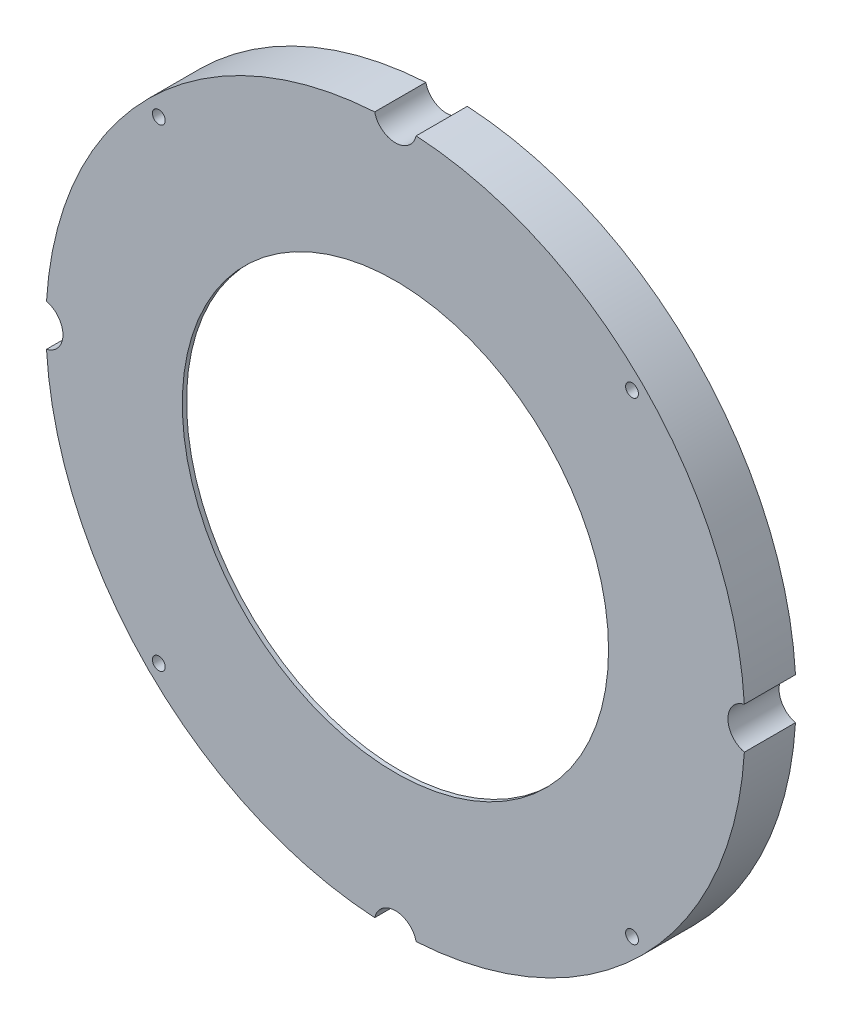
SolidWorks part; units mm, degrees
ref_plane "Front Plane" through (0, 0, 0) normal (0, 0, 1) x (1, 0, 0)
ref_plane "Top Plane" through (0, 0, 0) normal (0, 1, 0) x (1, 0, 0)
ref_plane "Right Plane" through (0, 0, 0) normal (1, 0, 0) x (0, 0, -1)
sketch "Sketch1" plane through (0, 0, 0) normal (0, 0, 1) x (1, 0, 0)
  circle A0 centre (0, 0) radius 50
  circle A1 centre (0, 0) radius 82
extrude "Boss-Extrude1" add sketch "Sketch1" along normal blind 1
sketch "Sketch3" plane through (0, 0, 0) normal (0, 0, -1) x (-1, 0, 0)
  circle A0 centre (0, 0) radius 75
  circle A1 centre (0, 0) radius 82
extrude "Boss-Extrude3" add sketch "Sketch3" along normal blind 11
sketch "Sketch4" plane through (0, 0, 1) normal (0, 0, 1) x (1, 0, 0)
  circle A0 centre (0, 83) radius 5
extrude "Cut-Extrude1" cut sketch "Sketch4" against normal through all
pattern_circular "CirPattern1" count 4 every 90 about axis through (0, 0, 0) along (0, 0, 1) of "Cut-Extrude1"
sketch "Sketch5" plane through (0, 0, -11) normal (0, 0, -1) x (-1, 0, 0)
  circle A0 centre (55.5079, 55.5079) radius 1.5
extrude "Cut-Extrude2" cut sketch "Sketch5" against normal through all
pattern_circular "CirPattern2" count 4 every 90 about axis through (0, 0, 0) along (0, 0, 1) of "Cut-Extrude2"
